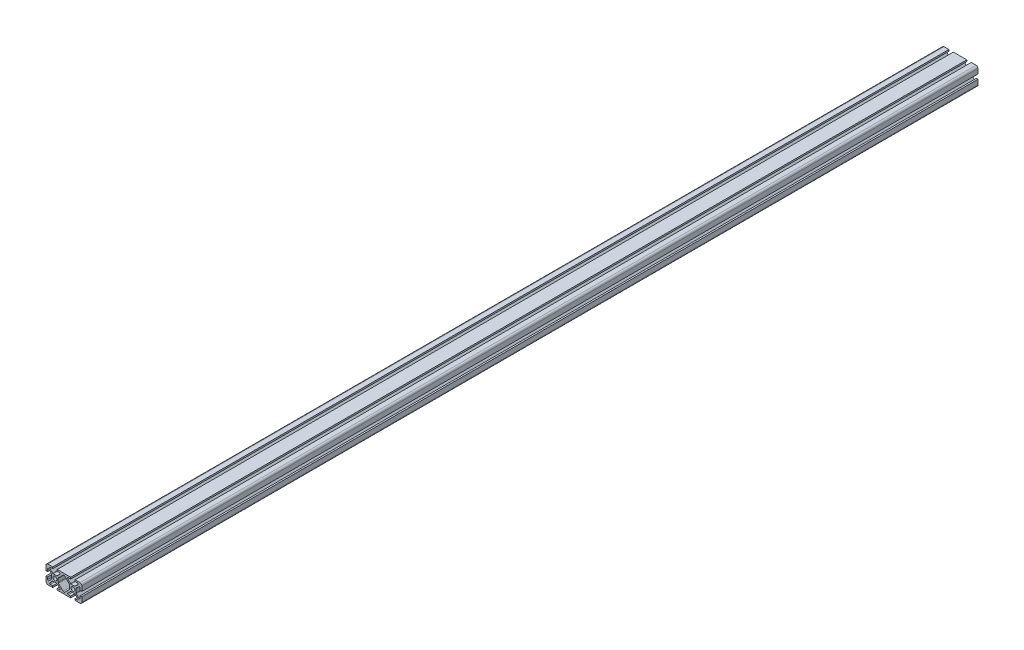
SolidWorks part; units mm, degrees
ref_plane "Front Plane" through (0, 0, 0) normal (0, 0, 1) x (1, 0, 0)
ref_plane "Top Plane" through (0, 0, 0) normal (0, 1, 0) x (1, 0, 0)
ref_plane "Right Plane" through (0, 0, 0) normal (1, 0, 0) x (0, 0, -1)
sketch "Sketch1" plane through (0, 0, 0) normal (0, 0, 1) x (1, 0, 0)
  line L0 (10, 10) -> (10, -10) construction
  line L1 (-20, 0) -> (20, 0) construction
  line L2 (12.5, -10) -> (20, -10)
  line L3 (20, -10) -> (20, -2.5)
  line L4 (12.5, -10) -> (12.5, -8.2134)
  line L5 (12.5, -8.2134) -> (16.95, -8.2134)
  line L6 (16.95, -8.2134) -> (12.3366, -3.6)
  line L7 (10, 0) -> (20, -10) construction
  line L8 (20, -2.5) -> (18.2134, -2.5)
  line L9 (18.2134, -2.5) -> (18.2134, -6.95)
  line L10 (18.2134, -6.95) -> (13.6, -2.3366)
  line L11 (15.9067, -4.6433) -> (14.6433, -5.9067) construction
  line L12 (0, 10) -> (0, -10) construction
  line L13 (0, -10) -> (-20, -10) construction
  line L14 (-10, 10) -> (10, 10) construction
  line L15 (20, 2.5) -> (20, -2.5) construction
  circle A0 centre (10, 0) radius 2.15
  arc A1 (15.5015, -8.2134) -> (15.9257, -7.1891) centre (15.5015, -7.6134) ccw construction
  point P8 (10, -3.6)
  point P16 (15.275, -5.275)
  point P30 (20, 0)
  dimension "Center Hole Diameter" = 4.3
  dimension "D3" = 0.6
  dimension "Rail Width" = 20
  dimension "T-Slot Width" = 5
  dimension "Slot Depth" = 6.4
  dimension "Rail Height" = 40
  dimension "Inner Slot Width" = 13.9
  dimension "Hole Spacing" = 20
sketch "Sketch2" plane through (0, 0, 0) normal (1, 0, 0) x (0, 0, -1)
  line L0 (-1524, -10) -> (1524, -10) construction
  line L1 (-1484, 0) -> (1484, 0) construction
  point P6 (-1484, 0)
  point P8 (1484, 0)
  dimension "Length" = 3048
  dimension "D1" = 40
sketch "Sketch3" plane through (0, 0, 0) normal (0, 0, 1) x (1, 0, 0)
  line L0 (12.5, -10) -> (17.9, -10)
  line L1 (12.5, -10) -> (20, -10) construction
  line L2 (12.5, -10) -> (12.5, -8.2134) construction
  line L3 (12.5, -8.2134) -> (16.95, -8.2134) construction
  line L4 (12.5, -8.2134) -> (12.5, -10)
  line L5 (12.5, -8.2134) -> (16.95, -8.2134)
  line L6 (10, -3.6) -> (12.3366, -3.6)
  line L7 (16.95, -8.2134) -> (12.3366, -3.6) construction
  line L8 (12.3366, -3.6) -> (16.95, -8.2134)
  line L9 (20, -10) -> (20, -2.5) construction
  line L10 (18.2134, -6.95) -> (13.6, -2.3366) construction
  line L11 (18.2134, -2.5) -> (18.2134, -6.95) construction
  line L12 (18.2134, -6.95) -> (18.2134, -2.5)
  line L13 (20, -2.5) -> (18.2134, -2.5) construction
  line L14 (18.2134, -2.5) -> (20, -2.5)
  line L15 (20, -2.5) -> (20, -7.9)
  line L16 (18.2134, -6.95) -> (13.6, -2.3366)
  line L17 (13.6, 0) -> (13.6, -2.3366)
  line L18 (-20, 0) -> (20, 0) construction
  line L19 (10, -3.6) -> (10, -2.15)
  line L20 (10, 10) -> (10, -10) construction
  line L21 (13.6, 0) -> (12.15, 0)
  arc A5 (17.9, -10) -> (20, -7.9) centre (17.9, -7.9) ccw
  circle A10 centre (10, 0) radius 2.15 construction
  arc A11 (10, -2.15) -> (12.15, 0) centre (10, 0) ccw
  dimension "D1" = 2.1
extrude "Boss-Extrude1" add sketch "Sketch3" along normal mid plane 3048
sketch "Sketch4" plane through (0, 0, 0) normal (0, 0, 1) x (1, 0, 0)
  line L0 (10, -3.6) -> (7.6634, -3.6)
  line L4 (7.6634, -3.6) -> (3.05, -8.2134)
  line L5 (3.05, -8.2134) -> (7.5, -8.2134)
  line L6 (7.5, -8.2134) -> (7.5, -10)
  line L18 (7.5, -10) -> (0, -10)
  line L19 (12.5, -10) -> (12.5, -8.2134) construction
  line L20 (12.5, -8.2134) -> (16.95, -8.2134) construction
  line L21 (10, -3.6) -> (12.3366, -3.6) construction
  line L22 (16.95, -8.2134) -> (12.3366, -3.6) construction
  line L23 (0, -8.7366) -> (6.4, -2.3366)
  line L24 (0, 10) -> (0, -10) construction
  line L25 (6.4, -2.3366) -> (6.4, 0)
  line L26 (-20, 0) -> (20, 0) construction
  line L27 (6.4, 0) -> (7.85, 0)
  line L28 (13.6, 0) -> (12.15, 0) construction
  line L29 (0, -8.7366) -> (0, -10)
  line L30 (10, -2.15) -> (10, -3.6)
  circle A4 centre (10, 0) radius 2.15 construction
  arc A5 (7.85, 0) -> (10, -2.15) centre (10, 0) ccw
extrude "Boss-Extrude2" add sketch "Sketch4" along normal mid plane 3048
mirror "Mirror1" about plane through (0, 0, 0) normal (1, 0, 0) of bodies 137 134
mirror "Mirror2" about plane through (0, 0, 0) normal (0, 1, 0) of bodies 135
fillet "Fillet1" radius 0.75 24 edges at (-7.6634, -3.6, 0) (-12.3366, -3.6, 0) (12.3366, -3.6, 0) (7.6634, -3.6, 0) (-3.05, -8.2134, 0) (-18.2134, -6.95, 0) (-16.95, -8.2134, 0) (-13.6, -2.3366, 0) (-18.2134, 6.95, 0) (-16.95, 8.2134, 0) (-12.3366, 3.6, 0) (-7.6634, 3.6, 0) (-13.6, 2.3366, 0) (-3.05, 8.2134, 0) (3.05, 8.2134, 0) (13.6, -2.3366, 0) (13.6, 2.3366, 0) (7.6634, 3.6, 0) (12.3366, 3.6, 0) (18.2134, 6.95, 0) (16.95, 8.2134, 0) (18.2134, -6.95, 0) (16.95, -8.2134, 0) (3.05, -8.2134, 0)
fillet "Fillet2" radius 1.25 6 edges at (0, -8.7366, 0) (-6.4, -2.3366, 0) (0, 8.7366, 0) (-6.4, 2.3366, 0) (6.4, -2.3366, 0) (6.4, 2.3366, 0)
sketch "Sketch5" plane through (-20, 0, 0) normal (-1, 0, 0) x (0, 0, 1)
  line L0 (1524, -10) -> (-1524, -10) construction
  line L1 (1524, 10) -> (-524, 10)
  line L2 (1524, 10) -> (1524, -10)
  line L3 (1524, -10) -> (-524, -10)
  line L4 (-524, 10) -> (-524, -10)
  dimension "D1" = 1000
extrude "Cut-Extrude1" cut sketch "Sketch5" against normal through all
equation "\"D1@Sketch3\" = \"D3@Sketch1\" * 3.5"
equation "\"D1@Boss-Extrude1\" = \"Length@Sketch2\""
equation "\"D1@Boss-Extrude2\" = \"Length@Sketch2\""
equation "\"D1@Sketch2\"=\"Rail Height@Sketch1\""
